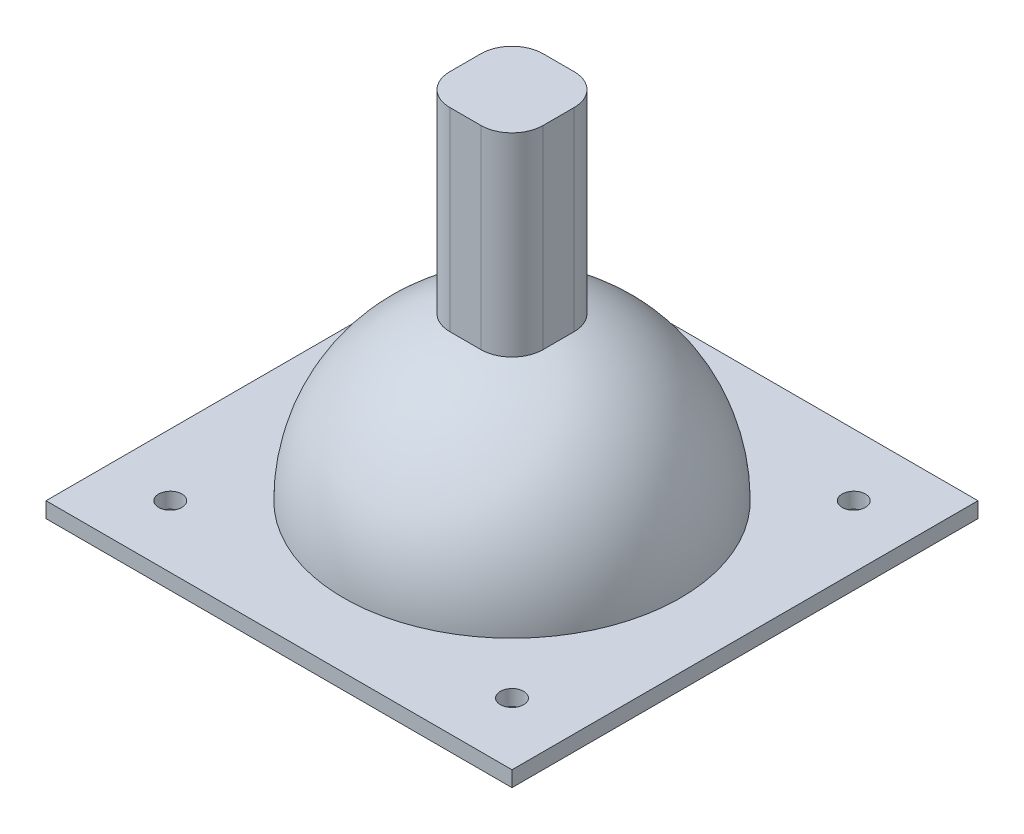
SolidWorks part; units mm, degrees
ref_plane "Front Plane" through (0, 0, 0) normal (0, 0, 1) x (1, 0, 0)
ref_plane "Top Plane" through (0, 0, 0) normal (0, 1, 0) x (1, 0, 0)
ref_plane "Right Plane" through (0, 0, 0) normal (1, 0, 0) x (0, 0, -1)
sketch "Sketch1" plane through (0, 0, 0) normal (0, 1, 0) x (1, 0, 0)
  line L1 (7.62, -7.62) -> (-7.62, -7.62)
  line L2 (7.62, -7.62) -> (7.62, 7.62)
  line L3 (7.62, 7.62) -> (-7.62, 7.62)
  line L4 (-7.62, -7.62) -> (-7.62, 7.62)
  line L5 (7.62, -7.62) -> (-7.62, 7.62) construction
  line L6 (7.62, 7.62) -> (-7.62, -7.62) construction
  point P0 (0, 0)
  dimension "D1" = 15.24
extrude "Boss-Extrude1" add sketch "Sketch1" along normal blind 31.75
fillet "Fillet1" radius 5.08 4 edges at (-7.62, 15.875, 7.62) (7.62, 15.875, 7.62) (7.62, 15.875, -7.62) (-7.62, 15.875, -7.62)
sketch "Sketch2" plane through (0, 0, 0) normal (0, -1, 0) x (1, 0, 0)
  line L1 (12.7, -12.7) -> (-12.7, -12.7)
  line L2 (12.7, -12.7) -> (12.7, 12.7)
  line L3 (12.7, 12.7) -> (-12.7, 12.7)
  line L4 (-12.7, -12.7) -> (-12.7, 12.7)
  line L5 (12.7, -12.7) -> (-12.7, 12.7) construction
  line L6 (12.7, 12.7) -> (-12.7, -12.7) construction
  point P0 (0, 0)
  dimension "D1" = 25.4
sketch "Sketch3" plane through (0, 0, 0) normal (1, 0, 0) x (0, 0, -1)
  line L2 (0, -1.2654) -> (0, -22.1401) construction
  line L4 (25.0068, -26.4719) -> (27.5468, -26.4719)
  line L5 (0, -1.4651) -> (0, 1.0749)
  arc A2 (25.0068, -26.4719) -> (0, -1.4651) centre (0, -26.4719) ccw
  circle A3 centre (0, -26.4719) radius 27.5468 construction
  arc A4 (27.5468, -26.4719) -> (0, 1.0749) centre (0, -26.4719) ccw
  circle A5 centre (0, -26.4719) radius 25.0068 construction
  dimension "D1" = 2.54
revolve "Revolve1" add sketch "Sketch3" angle 360 about L2
sketch "Sketch4" plane through (0, -26.4719, 0) normal (0, -1, 0) x (1, 0, 0)
  line L1 (38.1, -38.1) -> (-38.1, -38.1)
  line L2 (38.1, -38.1) -> (38.1, 38.1)
  line L3 (38.1, 38.1) -> (-38.1, 38.1)
  line L4 (-38.1, -38.1) -> (-38.1, 38.1)
  line L5 (38.1, -38.1) -> (-38.1, 38.1) construction
  line L6 (38.1, 38.1) -> (-38.1, -38.1) construction
  point P0 (0, 0)
  dimension "D1" = 76.2
extrude "Boss-Extrude2" add sketch "Sketch4" along normal blind 2.54
sketch "Sketch5" plane through (0, -29.0119, 0) normal (0, -1, 0) x (1, 0, 0)
  circle A0 centre (0, 0) radius 24.892
  dimension "D1" = 49.784
extrude "Cut-Extrude1" cut sketch "Sketch5" against normal up to surface (2.54 mm away) up to face at (0, -26.4719, 0)
sketch "Sketch6" plane through (0, -26.4719, 0) normal (0, 1, 0) x (1, 0, 0)
  line L0 (-27.94, 38.1) -> (-27.94, 27.94) construction
  line L1 (-38.1, 38.1) -> (38.1, 38.1) construction
  line L2 (-27.94, 27.94) -> (-38.1, 27.94) construction
  line L3 (-38.1, -38.1) -> (-38.1, 38.1) construction
  circle A0 centre (-27.94, 27.94) radius 1.905
  dimension "D2" = 3.81
  dimension "D1" = 10.16
extrude "Cut-Extrude2" cut sketch "Sketch6" against normal through all
pattern_linear "LPattern1" count 2 spacing 55.88 along (1, 0, 0) count 2 spacing 55.88 along (0, 0, 1) of "Cut-Extrude2"
